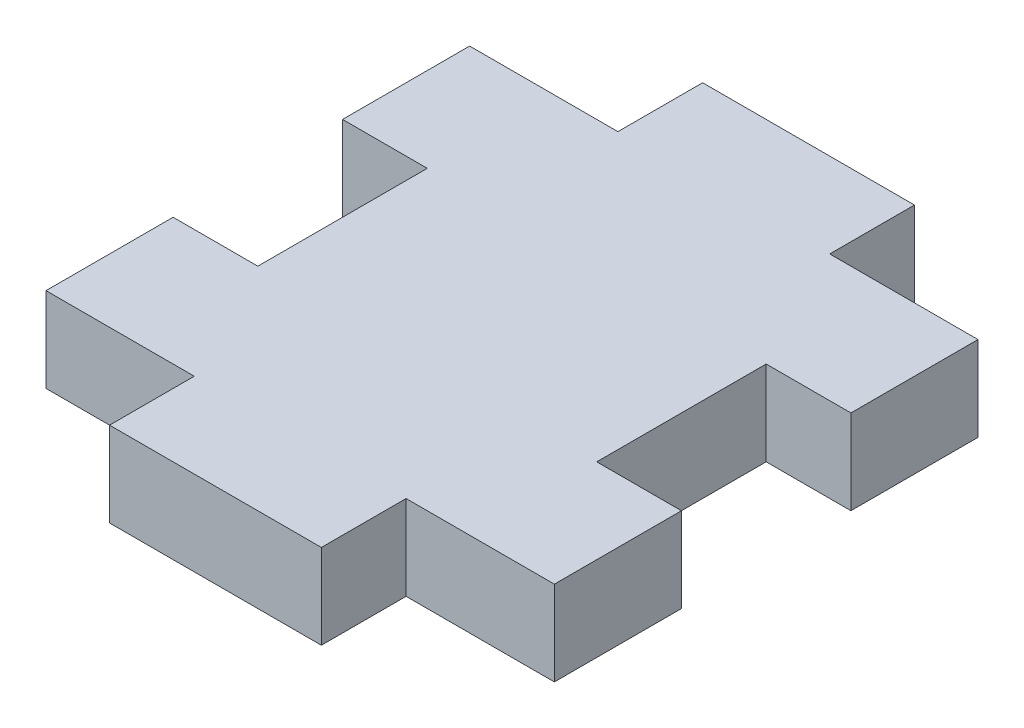
SolidWorks part; units mm, degrees
material "Acrylic (Medium-high impact)"
ref_plane "Front Plane" through (0, 0, 0) normal (0, 0, 1) x (1, 0, 0)
ref_plane "Top Plane" through (0, 0, 0) normal (0, 1, 0) x (1, 0, 0)
ref_plane "Right Plane" through (0, 0, 0) normal (1, 0, 0) x (0, 0, -1)
sketch "Sketch1" plane through (0, 0, 0) normal (0, 1, 0) x (1, 0, 0)
  line L0 (-15.875, -31.75) -> (-38.1, -31.75)
  line L1 (15.875, -44.45) -> (-15.875, -44.45)
  line L2 (15.875, -44.45) -> (15.875, -31.75)
  line L3 (15.875, 44.45) -> (-15.875, 44.45)
  line L4 (-15.875, -44.45) -> (-15.875, -31.75)
  line L5 (-15.875, 31.75) -> (-15.875, 44.45)
  line L6 (-15.875, 31.75) -> (-38.1, 31.75)
  line L7 (38.1, -31.75) -> (15.875, -31.75)
  line L8 (38.1, -31.75) -> (38.1, -12.7)
  line L9 (38.1, 31.75) -> (15.875, 31.75)
  line L10 (-38.1, -31.75) -> (-38.1, -12.7)
  line L11 (15.875, 31.75) -> (15.875, 44.45)
  line L12 (38.1, -12.7) -> (25.4, -12.7)
  line L13 (25.4, -12.7) -> (25.4, 12.7)
  line L14 (25.4, 12.7) -> (38.1, 12.7)
  line L15 (0, 0) -> (0, 11.5723) construction
  line L16 (-38.1, -12.7) -> (-25.4, -12.7)
  line L17 (-25.4, -12.7) -> (-25.4, 12.7)
  line L18 (-25.4, 12.7) -> (-38.1, 12.7)
  line L19 (-38.1, 12.7) -> (-38.1, 31.75)
  line L20 (38.1, 12.7) -> (38.1, 31.75)
  point P0 (0, 0)
  point P6 (0, 0)
  point P15 (0, 44.45)
  point P19 (25.4, 0)
  dimension "D1" = 31.75
  dimension "D3" = 76.2
  dimension "D5" = 12.7
  dimension "D2" = 12.7
  dimension "D4" = 88.9
  dimension "D6" = 25.4
  dimension "D7" = 12.7
extrude "Boss-Extrude1" add sketch "Sketch1" along normal blind 12.7 contours L7 L2 L1 L4 L0 L10 L16 L17 L18 L19 L6 L5 L3 L11 L9 L20 L14 L13 L12 L8
equation "\"D5@Sketch1\"=\"D2@Sketch1\""
